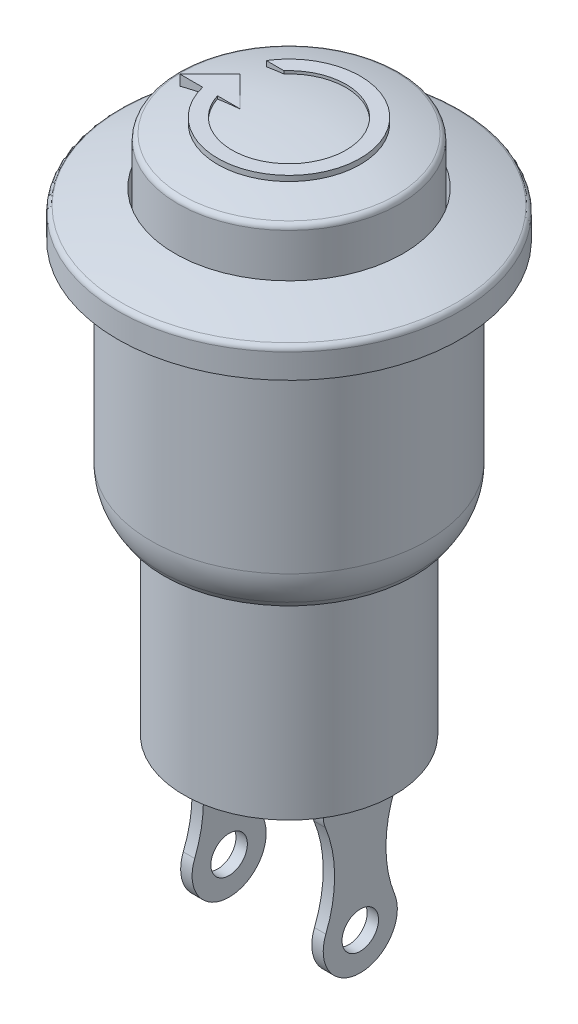
SolidWorks part; units mm, degrees
ref_plane "Plan de face" through (0, 0, 0) normal (0, 0, 1) x (1, 0, 0)
ref_plane "Plan de dessus" through (0, 0, 0) normal (0, 1, 0) x (1, 0, 0)
ref_plane "Plan de droite" through (0, 0, 0) normal (1, 0, 0) x (0, 0, -1)
sketch "Esquisse1" plane through (0, 0, 0) normal (0, 0, 1) x (1, 0, 0)
  line L0 (0, 0) -> (0, 22.281) construction
  line L1 (0, 0) -> (3.69, 0)
  line L2 (3.69, 0) -> (3.69, 7)
  line L3 (3.69, 7) -> (4.84, 7)
  line L4 (4.84, 7) -> (4.84, 15)
  line L5 (4.84, 15) -> (6.01, 15)
  line L6 (6.01, 15) -> (6.01, 16)
  line L7 (4, 16.6) -> (4, 15.0132)
  line L8 (4, 28.4891) -> (4, 11.2832) construction
  line L9 (4, 15.0132) -> (3.89, 15.0132)
  line L10 (3.89, 15.0132) -> (3.89, 18.2)
  line L11 (-3.8266, 18.8) -> (12.3412, 18.8) construction
  line L12 (0, 0) -> (0, -31.1321) construction
  line L13 (0, 18.8) -> (0, 0)
  arc A0 (4, 18.1647) -> (0, 18.8) centre (0, 5.8899) ccw
  arc A1 (6.01, 16) -> (4, 16.6) centre (0, -0.4667) ccw
  point P15 (4, 16.6)
  point P21 (0, 18.8)
  dimension "D1" = 7
  dimension "D2" = 7.38
  dimension "D3" = 9.68
  dimension "D4" = 8
  dimension "D5" = 18.2
  dimension "D6" = 12.02
  dimension "D7" = 1
  dimension "D8" = 4
  dimension "D9" = 18.8
  dimension "D10" = 7.78
  dimension "D11" = 16.6
revolve "Révolution1" add sketch "Esquisse1" angle 360 about L0
fillet "Congé1" radius 0.2 1 edges at (0, 18.2, -3.89)
fillet "Congé2" radius 0.2 1 edges at (0, 16, -6.01)
chamfer "Chanfrein1" distance 0.7 angle 33 1 edges at (0, 7, -4.84)
fillet "Congé3" radius 2 1 edges at (0, 7.7, -4.84)
sketch "Esquisse2" plane through (0, 0, 0) normal (0, -1, 0) x (1, 0, 0)
  line L0 (0, 0) -> (0, 6.3616) construction
  line L1 (2.1, 1.3) -> (2.1, -1.3)
  line L2 (-2.5, 1.3) -> (-2.1, 1.3)
  line L3 (-2.5, 1.3) -> (-2.5, -1.3)
  line L4 (-2.5, -1.3) -> (-2.1, -1.3)
  line L5 (-2.1, 1.3) -> (-2.1, -1.3)
  line L6 (2.5, -1.3) -> (2.1, -1.3)
  line L7 (2.5, 1.3) -> (2.5, -1.3)
  line L8 (2.5, 1.3) -> (2.1, 1.3)
  dimension "D1" = 0.4
  dimension "D2" = 2.6
  dimension "D3" = 1.3
  dimension "D4" = 2.5
extrude "Boss.-Extru.1" add sketch "Esquisse2" along normal blind 6
sketch "Esquisse3" plane through (-2.5, 0, 0) normal (-1, 0, 0) x (0, 0, 1)
  line L0 (-3.5285, -0.8) -> (6.6043, -0.8) construction
  line L1 (-3.69, 0) -> (3.69, 0) construction
  line L2 (-3.2571, -4) -> (6.2876, -4) construction
  line L3 (-1.3, -6) -> (-1.3, 0) construction
  line L4 (1.3, -6) -> (1.3, 0) construction
  line L5 (1.3, -6) -> (-1.3, -6) construction
  line L6 (0, 0) -> (0, -6.5355) construction
  line L7 (1.3, 0) -> (-1.3, 0) construction
  line L8 (-0.9, -1.0754) -> (-0.9, -4.4649) construction
  line L9 (-1.3, -0.8) -> (-4.1925, -0.8)
  line L10 (-4.1925, -0.8) -> (-4.1925, -7.4756)
  line L11 (-4.1925, -7.4756) -> (5.5728, -7.5751)
  line L12 (5.5728, -7.5751) -> (5.2253, -0.8)
  line L13 (5.2253, -0.8) -> (1.3, -0.8)
  arc A0 (-1.2076, -4.2185) -> (1.2076, -4.2185) centre (0, -4.7) ccw
  arc A1 (-1.2076, -4.2185) -> (-1.3, -0.8) centre (-5.2253, -2.6167) ccw
  arc A2 (1.2076, -4.2185) -> (1.3, -0.8) centre (5.2253, -2.6167) cw
  circle A3 centre (0, -4.7) radius 0.64
  point P14 (-1.3, -0.8)
  dimension "D3" = 1.28
  dimension "D1" = 0.8
  dimension "D2" = 4
  dimension ".9" = 0.9
extrude "Enlèv. mat.-Extru.1" cut sketch "Esquisse3" against normal blind 6
fillet "Congé4" radius 1 4 edges at (2.3, -0.8, 1.3) (-2.3, -0.8, 1.3) (2.3, -0.8, -1.3) (-2.3, -0.8, -1.3)
ref_plane "Plano1" through (0, 18.244, 0) normal (0, -1, 0) x (-1, 0, 0)
sketch "Esboço1" plane through (0, 18.244, 0) normal (0, -1, 0) x (-1, 0, 0)
  line L0 (1.1069, -0.6032) -> (1.9069, -0.6032)
  line L1 (3.2261, -0.6032) -> (2.1665, 0.4564)
  line L2 (2.1665, 0.4564) -> (1.1069, -0.6032)
  line L3 (1.4994, 1.3236) -> (2.1209, 1.3236)
  line L4 (2.4261, -0.6032) -> (3.2261, -0.6032)
  arc A0 (2.1209, 1.3236) -> (2.4261, -0.6032) centre (0, 0) ccw
  arc A1 (1.4994, 1.3236) -> (1.9069, -0.6032) centre (0, 0) ccw
  dimension "D1" = 5
  dimension "D2" = 4
  dimension "D3" = 0.8
  dimension "D4" = 0.8
  dimension "D5" = 45
  dimension "D6" = 45
extrude "Ressalto-extrusão1" add sketch "Esboço1" along normal mid plane 1
